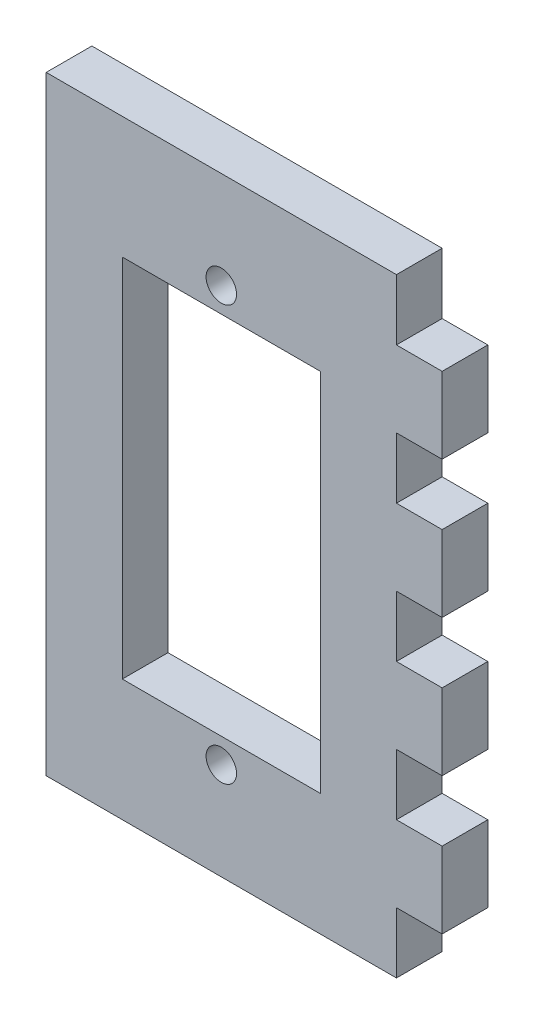
SolidWorks part; units mm, degrees
ref_plane "Front Plane" through (0, 0, 0) normal (0, 0, 1) x (1, 0, 0)
ref_plane "Top Plane" through (0, 0, 0) normal (0, 1, 0) x (1, 0, 0)
ref_plane "Right Plane" through (0, 0, 0) normal (1, 0, 0) x (0, 0, -1)
sketch "Sketch1" plane through (0, 0, 0) normal (0, 0, 1) x (1, 0, 0)
  line L0 (11.5, 16) -> (14.5, 16)
  line L1 (-11.5, -20) -> (11.5, -20)
  line L2 (-11.5, -20) -> (-11.5, 20)
  line L3 (-11.5, 20) -> (11.5, 20)
  line L4 (11.5, -20) -> (11.5, -16)
  line L5 (-11.5, -20) -> (11.5, 20) construction
  line L6 (-11.5, 20) -> (11.5, -20) construction
  line L7 (14.5, 16) -> (14.5, 11)
  line L8 (14.5, 11) -> (11.5, 11)
  line L9 (11.5, 7) -> (14.5, 7)
  line L10 (14.5, 7) -> (14.5, 2)
  line L11 (14.5, 2) -> (11.5, 2)
  line L12 (11.5, -16) -> (14.5, -16)
  line L13 (14.5, -16) -> (14.5, -11)
  line L14 (14.5, -11) -> (11.5, -11)
  line L15 (11.5, -7) -> (14.5, -7)
  line L16 (14.5, -7) -> (14.5, -2)
  line L17 (14.5, -2) -> (11.5, -2)
  line L18 (11.5, 16) -> (11.5, 20)
  line L19 (11.5, 7) -> (11.5, 11)
  line L20 (11.5, -2) -> (11.5, 2)
  line L21 (11.5, -11) -> (11.5, -7)
  line L22 (0, 0) -> (9.0994, 0) construction
  line L23 (6.5, -12) -> (-6.5, -12)
  line L24 (6.5, -12) -> (6.5, 12)
  line L25 (6.5, 12) -> (-6.5, 12)
  line L26 (-6.5, -12) -> (-6.5, 12)
  line L27 (6.5, -12) -> (-6.5, 12) construction
  line L28 (6.5, 12) -> (-6.5, -12) construction
  circle A0 centre (0, 13.625) radius 1
  circle A1 centre (0, -13.625) radius 1
  point P0 (0, 0)
  point P20 (0, 0)
  dimension "D5" = 2
  dimension "D1" = 40
  dimension "D2" = 4
  dimension "D3" = 24
  dimension "D4" = 13.625
  dimension "D6" = 13
  dimension "D7" = 23
  dimension "D8" = 3
extrude "Boss-Extrude1" add sketch "Sketch1" along normal blind 3
